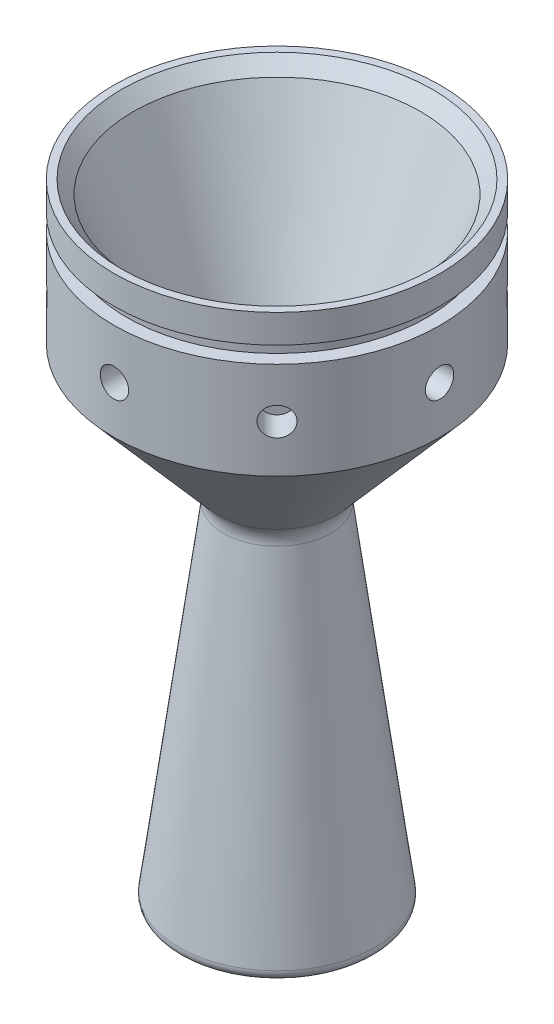
SolidWorks part; units mm, degrees
material "AISI 304"
ref_plane "Plano frontal" through (0, 0, 0) normal (0, 0, 1) x (1, 0, 0)
ref_plane "Plano superior" through (0, 0, 0) normal (0, 1, 0) x (1, 0, 0)
ref_plane "Plano direito" through (0, 0, 0) normal (1, 0, 0) x (0, 0, -1)
sketch "Esboço1" plane through (0, 0, 0) normal (0, 0, 1) x (1, 0, 0)
  line L0 (17.8119, -4.7739) -> (17.8119, 11.2487) construction
  line L1 (-13.6881, 0) -> (-16.6881, 0)
  line L2 (-16.6881, 0) -> (-16.6881, -6)
  line L4 (6.757, -56.9544) -> (-3.1624, -132.3)
  line L5 (-3.1624, -132.3) -> (-0.1881, -132.6916)
  line L6 (-0.1881, -132.6916) -> (9.8119, -56.734)
  line L7 (9.8119, -56.734) -> (-13.6881, 0)
  line L18 (-16.6881, -30) -> (6.757, -56.9544)
  line L19 (-16.6881, -6) -> (-13.8881, -6)
  line L20 (-13.8881, -6) -> (-13.8881, -9.5)
  line L21 (-13.8881, -9.5) -> (-16.6881, -9.5)
  line L22 (-16.6881, -9.5) -> (-16.6881, -30)
  dimension "D1" = 36
  dimension "D2" = 16
  dimension "D3" = 3
  dimension "D4" = 3
  dimension "D5" = 22.5
  dimension "D6" = 7.5
  dimension "D7" = 69
  dimension "D8" = 3.5
  dimension "D9" = 30
  dimension "D10" = 6
  dimension "D11" = 2.8
revolve "Revolução1" add sketch "Esboço1" angle 360 about L0
fillet "Filete4" radius 5 1 edges at (17.8119, -56.9544, -11.0549)
fillet "Filete5" radius 2 1 edges at (17.8119, -132.3, -20.9743)
fillet "Filete6" radius 2 1 edges at (17.8119, -56.734, -8)
ref_plane "Plano1" through (0, 0, -34.5) normal (0, 0, 1) x (1, 0, 0)
sketch "Esboço2" plane through (0, 0, -34.5) normal (0, 0, 1) x (1, 0, 0)
  line L0 (49.3119, 0) -> (-13.6881, 0) construction
  circle A0 centre (17.8119, -20) radius 3
  point P5 (0, 0)
  point P6 (0, 0)
  dimension "D1" = 6
  dimension "D2" = 20
extrude "Corte-extrusão1" cut sketch "Esboço2" along normal blind 6 contours A0
pattern_circular "PadrãoCircular1" count 8 over 360 about axis through (17.8119, 0, 0) along (0, 1, 0) of "Corte-extrusão1"
chamfer "Chanfro3" distance 3 angle 20 1 edges at (17.8119, 0, -31.5)
